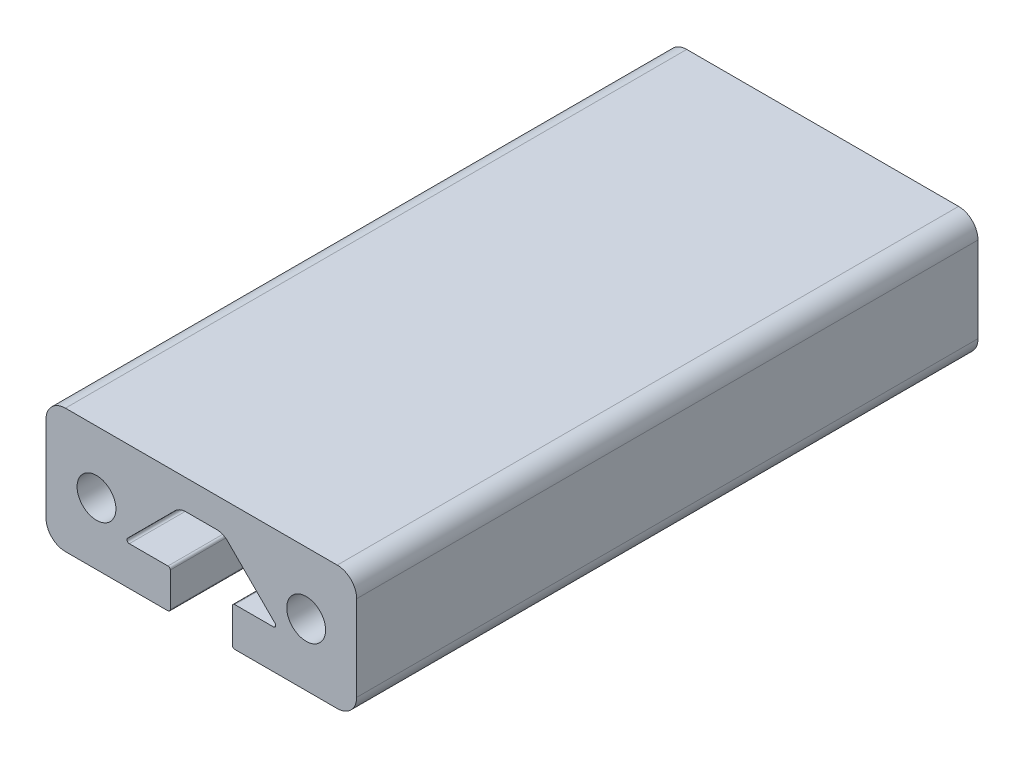
SolidWorks part; units mm, degrees
ref_plane "前视基准面" through (0, 0, 0) normal (0, 0, 1) x (1, 0, 0)
ref_plane "上视基准面" through (0, 0, 0) normal (0, 1, 0) x (1, 0, 0)
ref_plane "右视基准面" through (0, 0, 0) normal (1, 0, 0) x (0, 0, -1)
sketch "草图1" plane through (0, 0, 0) normal (0, 0, 1) x (1, 0, 0)
  line L0 (-2.4544, 4.6542) -> (1.4888, 4.6542)
  line L1 (2.903, 4.0684) -> (9.0051, -2.0337)
  line L2 (8.7929, -2.5458) -> (3.8172, -2.5458)
  line L3 (3.5172, -2.8458) -> (3.5172, -7.2458)
  line L4 (3.8172, -7.5458) -> (17.0172, -7.5458)
  line L5 (19.5172, -5.0458) -> (19.5172, 5.9542)
  line L6 (17.0172, 8.4542) -> (-17.9828, 8.4542)
  line L7 (-20.4828, 5.9542) -> (-20.4828, -5.0458)
  line L8 (-17.9828, -7.5458) -> (-4.7828, -7.5458)
  line L9 (-4.4828, -7.2458) -> (-4.4828, -2.8458)
  line L10 (-9.9707, -2.0337) -> (-3.8686, 4.0684)
  line L11 (-9.7585, -2.5458) -> (-4.7828, -2.5458)
  arc A0 (2.903, 4.0684) -> (1.4888, 4.6542) centre (1.4888, 2.6542) ccw
  arc A1 (8.7929, -2.5458) -> (9.0051, -2.0337) centre (8.7929, -2.2458) ccw
  arc A2 (3.8172, -2.5458) -> (3.5172, -2.8458) centre (3.8172, -2.8458) ccw
  arc A3 (3.5172, -7.2458) -> (3.8172, -7.5458) centre (3.8172, -7.2458) ccw
  arc A4 (17.0172, -7.5458) -> (19.5172, -5.0458) centre (17.0172, -5.0458) ccw
  arc A5 (19.5172, 5.9542) -> (17.0172, 8.4542) centre (17.0172, 5.9542) ccw
  arc A6 (-17.9828, 8.4542) -> (-20.4828, 5.9542) centre (-17.9828, 5.9542) ccw
  arc A7 (-20.4828, -5.0458) -> (-17.9828, -7.5458) centre (-17.9828, -5.0458) ccw
  arc A8 (-4.7828, -7.5458) -> (-4.4828, -7.2458) centre (-4.7828, -7.2458) ccw
  arc A9 (-2.4544, 4.6542) -> (-3.8686, 4.0684) centre (-2.4544, 2.6542) ccw
  arc A10 (-9.9707, -2.0337) -> (-9.7585, -2.5458) centre (-9.7585, -2.2458) ccw
  arc A11 (-4.4828, -2.8458) -> (-4.7828, -2.5458) centre (-4.7828, -2.8458) ccw
  circle A12 centre (-13.9828, 0.4542) radius 2.5
  circle A13 centre (13.0172, 0.4542) radius 2.5
extrude "凸台-拉伸1" add sketch "草图1" along normal blind 80
